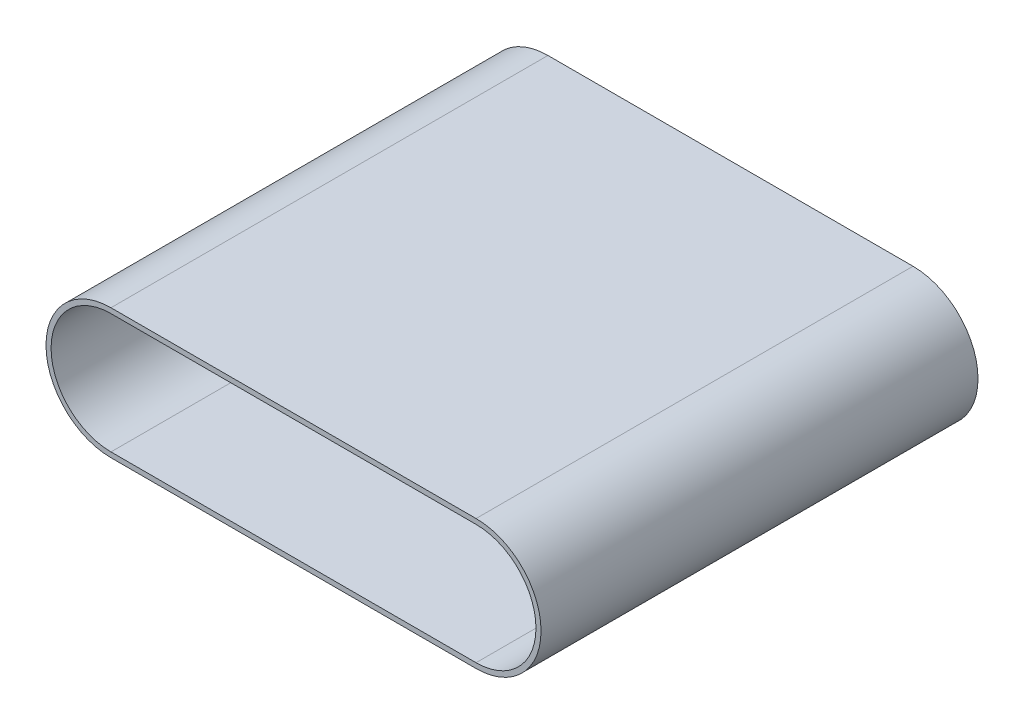
SolidWorks part; units mm, degrees
ref_plane "Front Plane" through (0, 0, 0) normal (0, 0, 1) x (1, 0, 0)
ref_plane "Top Plane" through (0, 0, 0) normal (0, 1, 0) x (1, 0, 0)
ref_plane "Right Plane" through (0, 0, 0) normal (1, 0, 0) x (0, 0, -1)
sketch "Sketch1" plane through (0, 0, 0) normal (0, 0, 1) x (1, 0, 0)
  line L0 (0, 9) -> (54.86, 9)
  line L1 (0, -9) -> (54.86, -9)
  arc A0 (0, 9) -> (0, -9) centre (0, 0) ccw
  arc A1 (54.86, -9) -> (54.86, 9) centre (54.86, 0) ccw
  point P9 (36.3594, -9)
  point P10 (0, 0)
  dimension "D1" = 18
  dimension "D2" = 18
  dimension "D3" = 54.86
extrude "Extrude-Thin1" add sketch "Sketch1" along normal blind 65.66 thin thin type one direction wall 0.762
